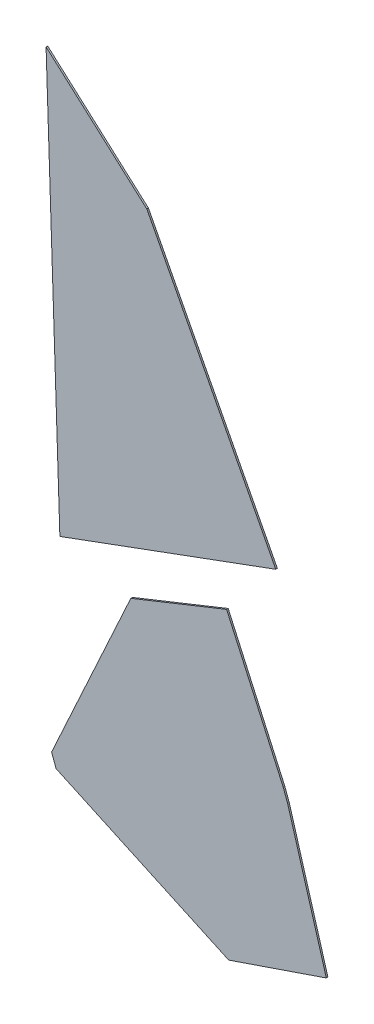
SolidWorks part; units mm, degrees
ref_plane "Front Plane" through (0, 0, 0) normal (0, 0, 1) x (1, 0, 0)
ref_plane "Top Plane" through (0, 0, 0) normal (0, 1, 0) x (1, 0, 0)
ref_plane "Right Plane" through (0, 0, 0) normal (1, 0, 0) x (0, 0, -1)
sketch "Sketch1" plane through (0, 0, 0) normal (0, 0, 1) x (1, 0, 0)
  line L0 (229.6667, 838) -> (1148.3333, 838) construction
sketch "Sketch3" plane through (0, 0, 0) normal (0, 0, 1) x (1, 0, 0)
  line L0 (24.3893, 16.4299) -> (57.7466, 28.7131)
  line L1 (24.3893, 16.4299) -> (22.2568, 80.8655)
  line L3 (37.8224, 66.9639) -> (57.7466, 28.7131)
  line L4 (22.2568, 80.8655) -> (37.8224, 66.9639)
extrude "Boss-Extrude1" add sketch "Sketch3" along normal blind 0.25
sketch "Sketch5" plane through (0, 0, 0) normal (0, 0, 1) x (1, 0, 0)
  line L0 (24.1178, 24.6343) -> (54.1172, 35.681) construction
  line L1 (24.3893, 16.4299) -> (22.2568, 80.8655) construction
  line L2 (37.8224, 66.9639) -> (57.7466, 28.7131) construction
  line L3 (24.3893, 16.4299) -> (57.7466, 28.7131) construction
  circle A0 centre (42.1581, 31.2773) radius 0.25
  circle A1 centre (32.0403, 27.5516) radius 0.25
  dimension "D1" = 0.5
sketch "Sketch6" plane through (0, 0, 0) normal (0, 0, 1) x (1, 0, 0)
  line L0 (23.1075, -13.061) -> (58.8762, 0.1818)
  line L1 (58.8762, 0.1818) -> (50.1461, 19.5448) construction
  line L2 (58.8762, 0.1818) -> (50.1461, 19.5448)
  line L3 (35.3488, 13.6279) -> (23.1075, -13.061)
  line L4 (35.3488, 13.6279) -> (50.1461, 19.5448)
  line L5 (44.1562, 32.8302) -> (21.8367, 82.3343) construction
  point P3 (35.4642, 13.9212)
  point P7 (23.3444, -12.9732)
  point P8 (0, 0)
  point P9 (33.7328, 10.0544)
  point P10 (58.9435, 0)
  point P11 (34.714, 10.2853)
  point P12 (23.1075, -13.061)
  point P13 (35.3488, 13.6279)
extrude "Boss-Extrude2" add sketch "Sketch6" along normal blind 0.25 separate body
sketch "Sketch7" plane through (0, 0, 0.25) normal (0, 0, 1) x (1, 0, 0)
  line L0 (23.1075, -13.061) -> (23.4547, -13.9987)
  line L1 (23.4547, -13.9987) -> (59.2234, -0.756)
  line L2 (59.2234, -0.756) -> (58.8762, 0.1818)
  line L4 (35.3488, 13.6279) -> (23.1075, -13.061)
  line L5 (23.1075, -13.061) -> (58.8762, 0.1818)
  line L6 (58.8762, 0.1818) -> (50.1461, 19.5448)
  line L7 (50.1461, 19.5448) -> (35.3488, 13.6279)
  line L9 (23.1075, -13.061) -> (58.8762, 0.1818)
  dimension "D2" = 1
  dimension "D1" = 0
extrude "Boss-Extrude3" add sketch "Sketch7" against normal up to surface (0.25 mm away) up to face at (41.8697, 5.0734, 0)
mirror "Mirror1" about plane through (23.4547, -13.9987, -38.8001) normal (0.3472, -0.9378, 0) of bodies 104
